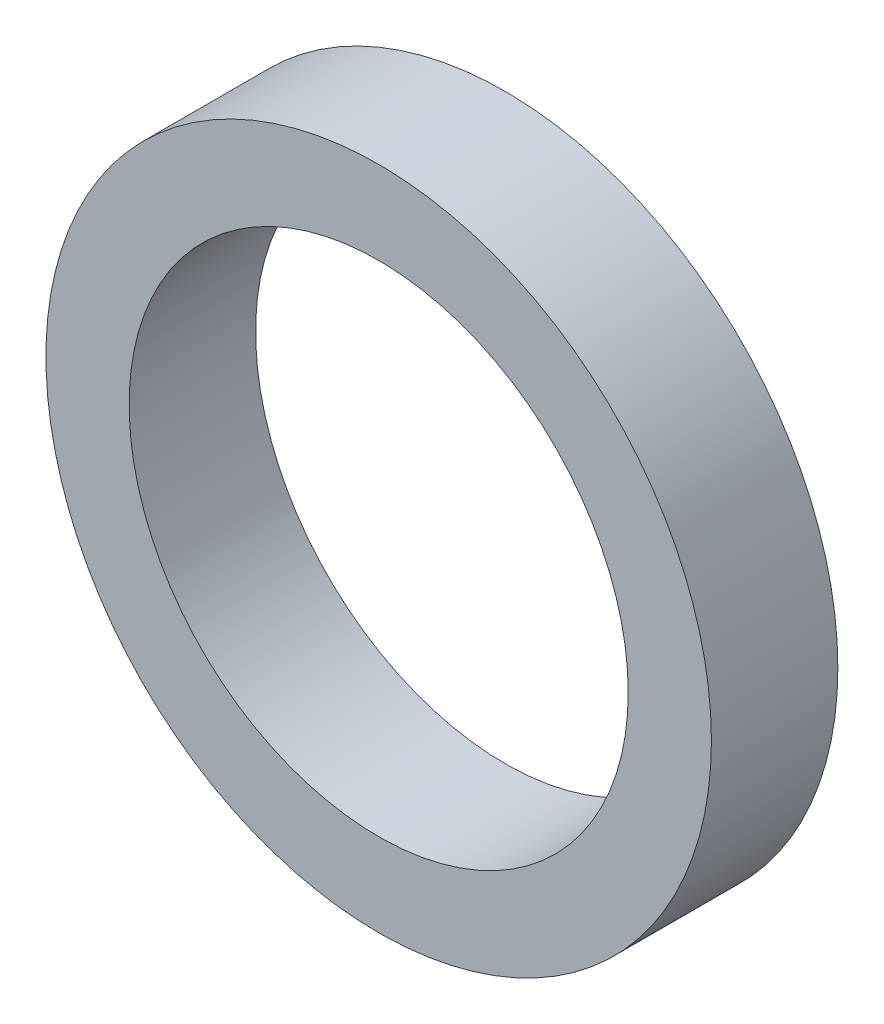
SolidWorks part; units mm, degrees
ref_plane "Front" through (0, 0, 0) normal (0, 0, 1) x (1, 0, 0)
ref_plane "Top" through (0, 0, 0) normal (0, 1, 0) x (1, 0, 0)
ref_plane "Right" through (0, 0, 0) normal (1, 0, 0) x (0, 0, -1)
sketch "Skizze1" plane through (0, 0, 0) normal (0, 0, 1) x (1, 0, 0)
  circle A0 centre (0, 0) radius 37.5
  circle A1 centre (0, 0) radius 50
  dimension "D1" = 75
  dimension "D2" = 100
extrude "Aufsatz-Linear austragen1" add sketch "Skizze1" along normal blind 19
